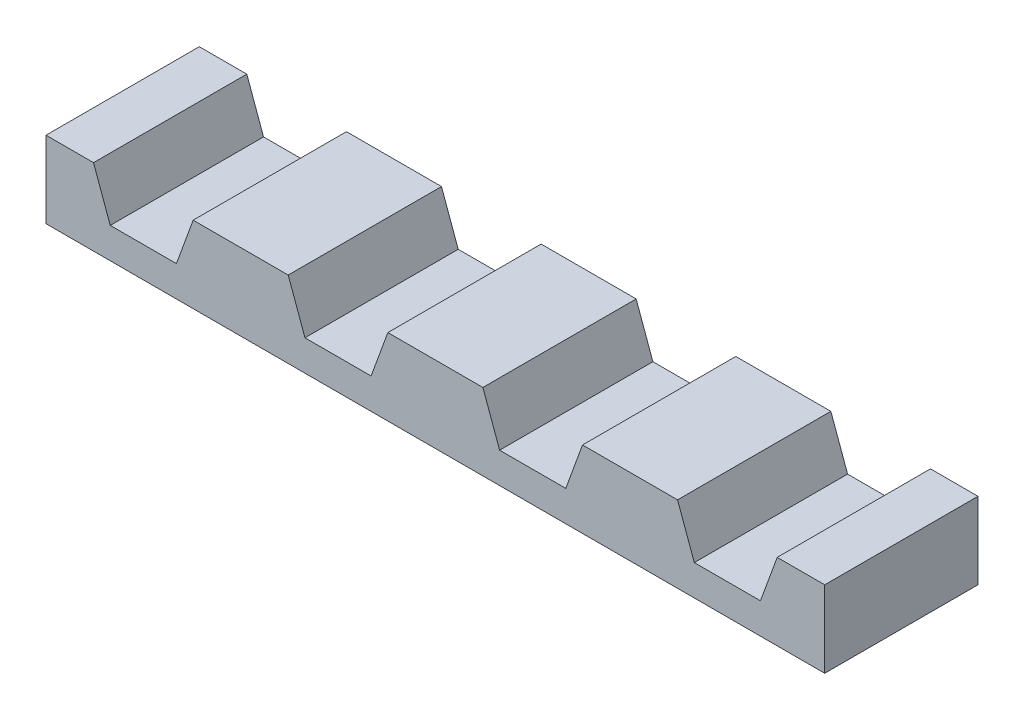
SolidWorks part; units mm, degrees
ref_plane "Front Plane" through (0, 0, 0) normal (0, 0, 1) x (1, 0, 0)
ref_plane "Top Plane" through (0, 0, 0) normal (0, 1, 0) x (1, 0, 0)
ref_plane "Right Plane" through (0, 0, 0) normal (1, 0, 0) x (0, 0, -1)
sketch "Sketch1" plane through (0, 0, 0) normal (0, 0, 1) x (1, 0, 0)
  line L1 (0, 0) -> (50.8, 0)
  line L2 (0, 0) -> (0, 5)
  line L3 (0, 5) -> (50.8, 5)
  line L4 (50.8, 0) -> (50.8, 5)
  dimension "D1" = 5
  dimension "D2" = 50.8
extrude "Boss-Extrude1" add sketch "Sketch1" along normal blind 10
sketch "Sketch3" plane through (0, 0, 10) normal (0, 0, 1) x (1, 0, 0)
  line L0 (2.0081, 8) -> (4.1919, 2)
  line L1 (4.1919, 2) -> (8.5081, 2)
  line L2 (8.5081, 2) -> (10.6919, 8)
  line L3 (10.6919, 8) -> (2.0081, 8)
  line L4 (3.1, 5) -> (9.6, 5) construction
  line L5 (50.8, 5) -> (0, 5) construction
  line L6 (0, 5) -> (0, 0) construction
  point P8 (0.9859, 6.406)
  point P9 (3.1, 5)
  point P10 (2.0412, 2)
  point P11 (0, 0)
  point P16 (6.35, 2)
  dimension "D1" = 6.5
  dimension "D2" = 40
  dimension "D3" = 3
  dimension "D4" = 6.35
extrude "Cut-Extrude2" cut sketch "Sketch3" against normal through all
pattern_linear "LPattern1" count 4 spacing 12.7 along (1, 0, 0) of "Cut-Extrude2"
